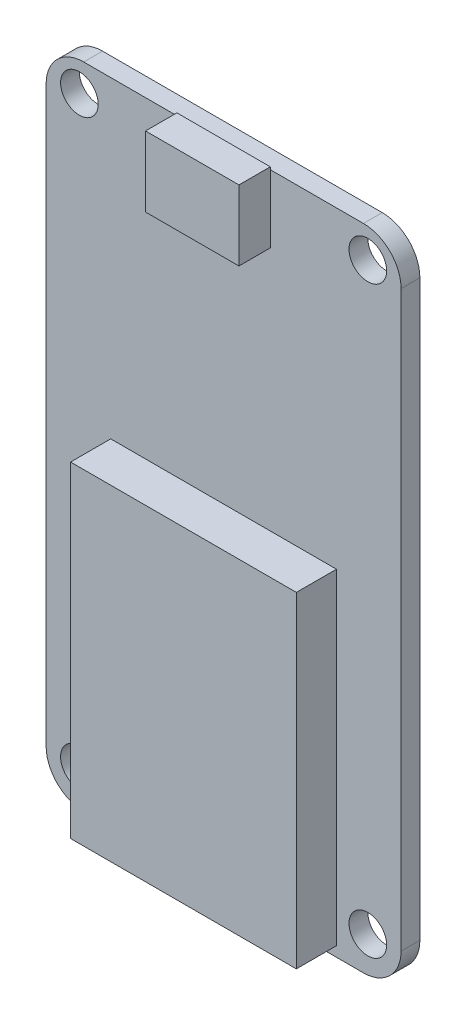
SolidWorks part; units mm, degrees
ref_plane "Front Plane" through (0, 0, 0) normal (0, 0, 1) x (1, 0, 0)
ref_plane "Top Plane" through (0, 0, 0) normal (0, 1, 0) x (1, 0, 0)
ref_plane "Right Plane" through (0, 0, 0) normal (1, 0, 0) x (0, 0, -1)
sketch "Sketch1" plane through (0, 0, 0) normal (0, 0, 1) x (1, 0, 0)
  line L0 (2.65, 49.4) -> (0, 49.4) construction
  line L1 (0, 0) -> (28.3, 0)
  line L2 (0, 0) -> (0, 51.75)
  line L3 (0, 51.75) -> (28.3, 51.75)
  line L4 (28.3, 0) -> (28.3, 51.75)
  line L5 (0, 0) -> (28.3, 51.75) construction
  line L6 (0, 51.75) -> (28.3, 0) construction
  line L7 (25.65, 49.4) -> (28.3, 49.4) construction
  line L8 (2.65, 2.85) -> (0, 2.85) construction
  line L9 (25.65, 2.85) -> (28.3, 2.85) construction
  circle A0 centre (2.65, 49.4) radius 1.5
  circle A1 centre (25.65, 49.4) radius 1.5
  circle A2 centre (2.65, 2.85) radius 1.5
  circle A3 centre (25.65, 2.85) radius 1.5
  point P4 (14.15, 25.875)
  dimension "D5" = 3
  dimension "D7" = 3
  dimension "D1" = 51.75
  dimension "D2" = 28.3
  dimension "D3" = 23
  dimension "D4" = 2.35
  dimension "D6" = 2.85
extrude "Boss-Extrude1" add sketch "Sketch1" along normal blind 1.5
fillet "Fillet1" radius 3 4 edges at (0, 0, 0.75) (28.3, 0, 0.75) (28.3, 51.75, 0.75) (0, 51.75, 0.75)
sketch "Sketch2" plane through (0, 0, 1.5) normal (0, 0, 1) x (1, 0, 0)
  line L0 (3, 0) -> (25.3, 0) construction
  line L1 (5.15, 26.8) -> (23.15, 26.8)
  line L2 (5.15, 26.8) -> (5.15, 0.8)
  line L3 (5.15, 0.8) -> (23.15, 0.8)
  line L4 (23.15, 26.8) -> (23.15, 0.8)
  line L5 (5.15, 26.8) -> (23.15, 0.8) construction
  line L6 (5.15, 0.8) -> (23.15, 26.8) construction
  line L7 (5.15, 12.4202) -> (0, 12.4202) construction
  line L8 (0, 48.75) -> (0, 3) construction
  line L9 (23.15, 11.871) -> (28.3, 11.871) construction
  line L10 (28.3, 3) -> (28.3, 48.75) construction
  point P4 (14.15, 13.8)
  dimension "D1" = 18
  dimension "D2" = 26
  dimension "D3" = 0.8
extrude "Boss-Extrude2" add sketch "Sketch2" along normal blind 3.2
sketch "Sketch3" plane through (0, 0, 1.5) normal (0, 0, 1) x (1, 0, 0)
  line L0 (17.875, 48.0543) -> (28.3, 48.0543) construction
  line L1 (17.875, 46.35) -> (10.425, 46.35)
  line L2 (17.875, 46.35) -> (17.875, 51.95)
  line L3 (17.875, 51.95) -> (10.425, 51.95)
  line L4 (10.425, 46.35) -> (10.425, 51.95)
  line L5 (17.875, 46.35) -> (10.425, 51.95) construction
  line L6 (17.875, 51.95) -> (10.425, 46.35) construction
  line L7 (28.3, 3) -> (28.3, 48.75) construction
  line L8 (10.425, 48.0543) -> (0, 48.0543) construction
  line L9 (0, 48.75) -> (0, 3) construction
  line L10 (25.3, 51.75) -> (3, 51.75) construction
  point P4 (14.15, 49.15)
  dimension "D1" = 7.45
  dimension "D2" = 5.6
  dimension "D3" = 0.2
extrude "Boss-Extrude3" add sketch "Sketch3" along normal blind 2.5
